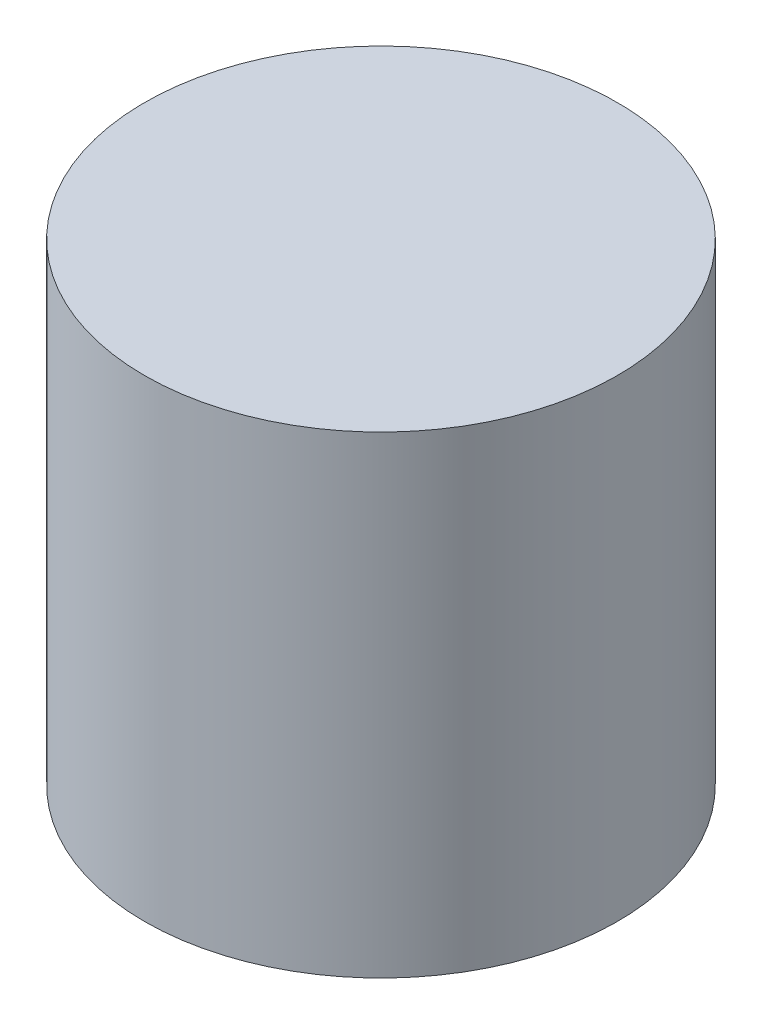
SolidWorks part; units mm, degrees
ref_plane "Plan de face" through (0, 0, 0) normal (0, 0, 1) x (1, 0, 0)
ref_plane "Plan de dessus" through (0, 0, 0) normal (0, 1, 0) x (1, 0, 0)
ref_plane "Plan de droite" through (0, 0, 0) normal (1, 0, 0) x (0, 0, -1)
sketch "Esquisse14" plane through (0, 0, 0) normal (0, 1, 0) x (1, 0, 0)
  circle A0 centre (0, 0) radius 50
extrude "Boss.-Extru.2" add sketch "Esquisse14" along normal blind 100
ref_plane "Plan4" through (0, 50, 0) normal (0, 1, 0) x (1, 0, 0)
ref_plane "Plan5" through (0, 0, 0) normal (0, 1, 0) x (1, 0, 0)
sketch "Esquisse17" plane through (0, 100, 0) normal (0, 1, 0) x (1, 0, 0)
  circle A0 centre (0, 0) radius 15.507
sketch "Esquisse18" plane through (0, 50, 0) normal (0, 1, 0) x (1, 0, 0)
  circle A0 centre (0, 0) radius 20.6799
sketch "Esquisse19" plane through (0, 0, 0) normal (0, 1, 0) x (1, 0, 0)
  circle A0 centre (0, 0) radius 37.3769
ref_plane "Plan6" through (0, 25, 0) normal (0, -1, 0) x (-1, 0, 0)
sketch "Esquisse20" plane through (0, 25, 0) normal (0, -1, 0) x (-1, 0, 0)
  circle A0 centre (0, 0) radius 15
ref_plane "Plan7" through (0, 75, 0) normal (0, 1, 0) x (1, 0, 0)
sketch "Esquisse22" plane through (0, 75, 0) normal (0, 1, 0) x (1, 0, 0)
  circle A0 centre (0, 0) radius 20
sketch "Esquisse25" plane through (0, 0, 0) normal (0, 0, 1) x (1, 0, 0)
  line L0 (15.507, 100) -> (-15.507, 100) construction
  line L1 (50, 100) -> (-50, 100) construction
  line L2 (20, 75) -> (-20, 75) construction
  line L3 (20.6799, 50) -> (-20.6799, 50) construction
  line L4 (-15, 25) -> (15, 25) construction
  line L5 (-55, 25) -> (55, 25) construction
  line L6 (37.3769, 0) -> (-37.3769, 0) construction
  spline S0 degree 3 poles (-15.507, 100) (-17.7876, 83.6537) (-29.99, 47.152) (-2.8044, 10.2917) (-37.3769, 0) knots 0 0 0 0 0.459949 1 1 1 1
sketch "Esquisse29" plane through (0, 0, 0) normal (0, 0, 1) x (1, 0, 0)
  line L0 (15.507, 100) -> (-15.507, 100) construction
  line L1 (50, 100) -> (-50, 100) construction
  line L2 (20, 75) -> (-20, 75) construction
  line L3 (55, 75) -> (-55, 75) construction
  line L4 (20.6799, 50) -> (-20.6799, 50) construction
  line L5 (-15, 25) -> (15, 25) construction
  line L6 (-55, 25) -> (55, 25) construction
  line L7 (37.3769, 0) -> (-37.3769, 0) construction
  spline S0 degree 3 poles (15.507, 100) (17.7876, 83.6537) (29.99, 47.152) (2.8044, 10.2917) (37.3769, 0) knots 0 0 0 0 0.459949 1 1 1 1
